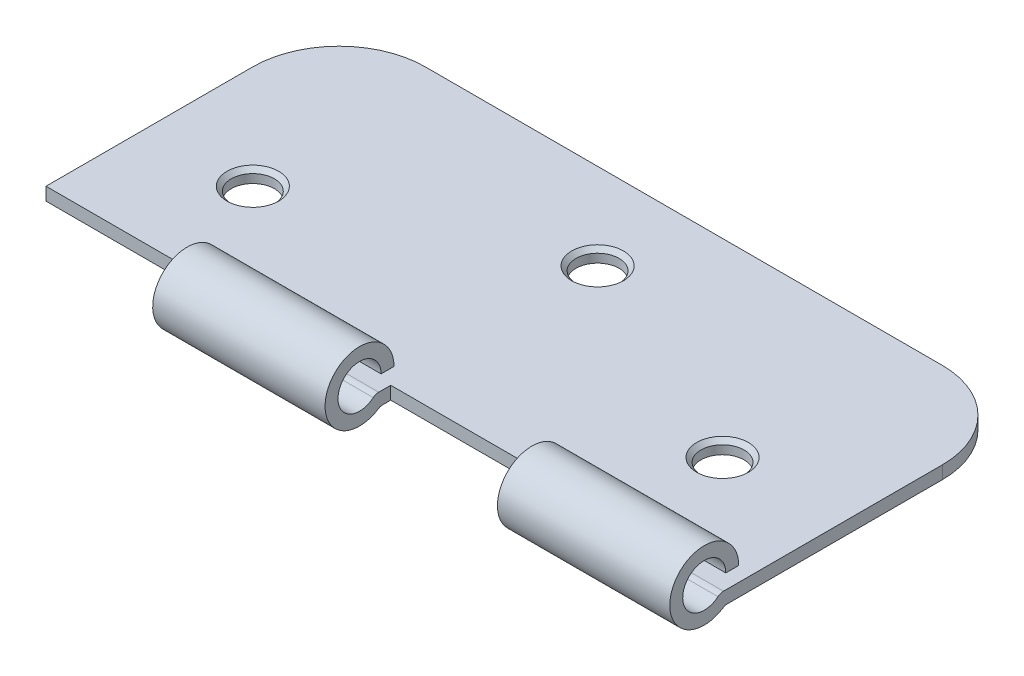
SolidWorks part; units mm, degrees
ref_plane "Front Plane" through (0, 0, 0) normal (0, 0, 1) x (1, 0, 0)
ref_plane "Top Plane" through (0, 0, 0) normal (0, 1, 0) x (1, 0, 0)
ref_plane "Right Plane" through (0, 0, 0) normal (1, 0, 0) x (0, 0, -1)
sketch "Sketch1" plane through (0, 0, 0) normal (0, 1, 0) x (1, 0, 0)
  line L1 (-30, 17) -> (30, 17)
  line L2 (-40, 7) -> (-40, -17)
  line L3 (-40, -17) -> (40, -17)
  line L4 (40, 7) -> (40, -17)
  line L5 (-40, 17) -> (40, -17) construction
  line L6 (-40, -17) -> (40, 17) construction
  arc A0 (-30, 17) -> (-40, 7) centre (-30, 7) ccw
  arc A1 (30, 17) -> (40, 7) centre (30, 7) cw
  point P0 (0, 0)
  dimension "D3" = 10
  dimension "D1" = 80
  dimension "D2" = 34
extrude "Boss-Extrude1" add sketch "Sketch1" along normal blind 1.5
sketch "Sketch3" plane through (40, 0, 0) normal (1, 0, 0) x (0, 0, -1)
  line L0 (-17, 0) -> (-17.9077, 0)
  line L1 (-17, 1.5) -> (-18.3935, 1.5)
  line L2 (-18.1209, 3.1998) -> (-16.6209, 3.1998)
  line L7 (-17, 0) -> (7, 0)
  line L8 (7, 0) -> (7, 1.5)
  line L9 (7, 1.5) -> (-17, 1.5)
  line L10 (-17, 1.5) -> (-17, 0)
  line L14 (-17, 1.5) -> (-17, 0)
  arc A0 (-16.6209, 3.1998) -> (-18.4503, -0.16) centre (-20.6209, 3.1998) ccw
  arc A1 (-18.1209, 3.1998) -> (-19.0299, 1.2714) centre (-20.6209, 3.1998) ccw
  arc A2 (-17.9077, 0) -> (-18.4503, -0.16) centre (-17.9077, -1) ccw
  arc A3 (-18.3935, 1.5) -> (-19.0299, 1.2714) centre (-18.3935, 0.5) ccw
  dimension "D1" = 8
  dimension "D2" = 5
  dimension "D3" = 1
  dimension "D4" = 0
extrude "Boss-Extrude2" add sketch "Sketch3" against normal blind 20
pattern_linear "LPattern1" count 2 spacing 40 along (-1, 0, 0) of "Boss-Extrude2"
sketch "Sketch6" plane through (0, 1.5, 0) normal (0, 1, 0) x (1, 0, 0)
  line L0 (40, -18.3935) -> (40, 7) construction
  line L1 (0, -17) -> (20, -17) construction
  line L2 (-40, -17) -> (-20, -17) construction
  line L3 (-40, 7) -> (-40, -17) construction
  circle A0 centre (-28, -5) radius 2.5
  circle A1 centre (0, 7) radius 2.5
  circle A2 centre (26.5, -5) radius 2.5
  point P8 (0, 0)
  point P10 (40.9747, 3.2303)
  point P12 (0, 0)
  point P14 (1.3415, -3.2167)
  dimension "D1" = 5
  dimension "D2" = 5
  dimension "D3" = 5
  dimension "D4" = 13.5
  dimension "D5" = 12
  dimension "D6" = 40
  dimension "D7" = 24
  dimension "D8" = 12
  dimension "D9" = 12
extrude "Cut-Extrude1" cut sketch "Sketch6" against normal blind 20
chamfer "Chamfer2" distance 0.5 angle 45 3 edges at (26.5, 1.5, 7.5) (0, 1.5, -4.5) (-28, 1.5, 7.5)
